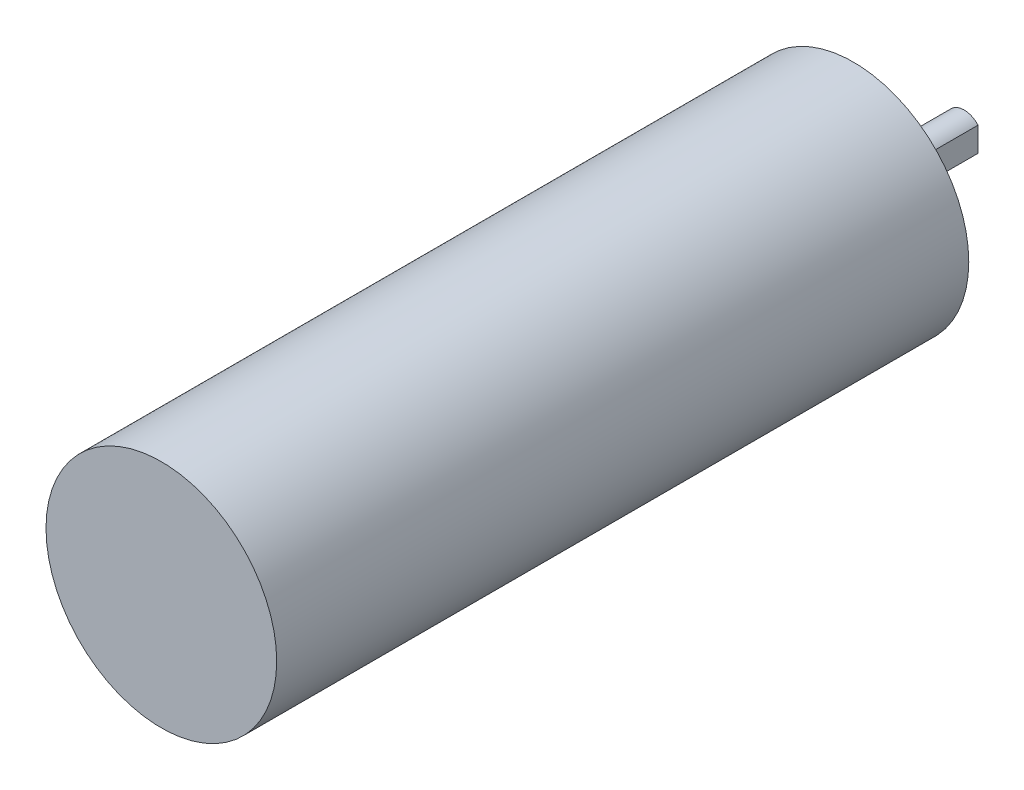
SolidWorks part; units mm, degrees
ref_plane "Front Plane" through (0, 0, 0) normal (0, 0, 1) x (1, 0, 0)
ref_plane "Top Plane" through (0, 0, 0) normal (0, 1, 0) x (1, 0, 0)
ref_plane "Right Plane" through (0, 0, 0) normal (1, 0, 0) x (0, 0, -1)
sketch "Sketch1" plane through (0, 0, 0) normal (0, 0, 1) x (1, 0, 0)
  circle A0 centre (0, 0) radius 2
extrude "Shaft" add sketch "Sketch1" along normal blind 12
ref_plane "Plane_z12" through (0, 0, 12) normal (0, 0, 1) x (1, 0, 0)
sketch "Sketch2" plane through (0, 0, 12) normal (0, 0, 1) x (1, 0, 0)
  circle A0 centre (0, 0) radius 12.5
extrude "Body" add sketch "Sketch2" along normal blind 75
sketch "Sketch3" plane through (0, 0, 0) normal (0, 0, 1) x (1, 0, 0)
  line L1 (1.5, -3) -> (4.5, -3)
  line L2 (1.5, -3) -> (1.5, 3)
  line L3 (1.5, 3) -> (4.5, 3)
  line L4 (4.5, -3) -> (4.5, 3)
extrude "D_flat" cut sketch "Sketch3" along normal blind 10
